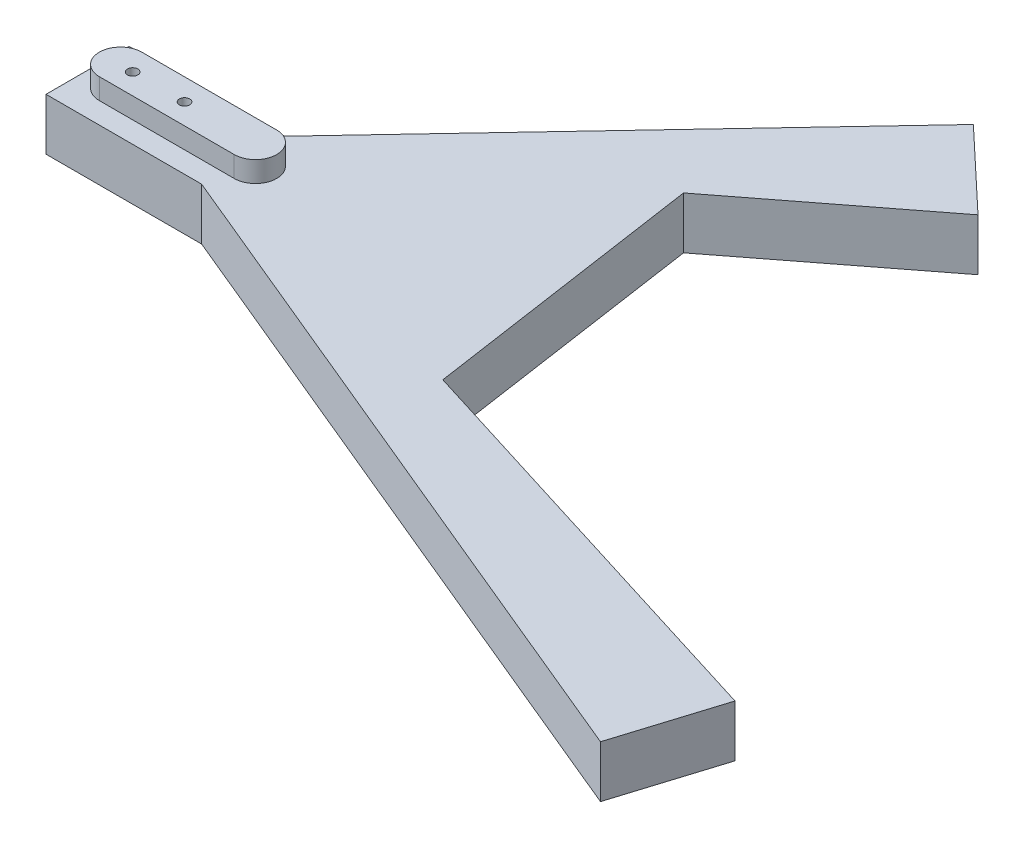
SolidWorks part; units mm, degrees
ref_plane "Front Plane" through (0, 0, 0) normal (0, 0, 1) x (1, 0, 0)
ref_plane "Top Plane" through (0, 0, 0) normal (0, 1, 0) x (1, 0, 0)
ref_plane "Right Plane" through (0, 0, 0) normal (1, 0, 0) x (0, 0, -1)
sketch "Sketch1" plane through (0, 0, 0) normal (0, 1, 0) x (1, 0, 0)
  line L0 (19.1887, 4.5283) -> (83.5984, 72.8611)
  line L1 (-10.8113, 4.5283) -> (19.1887, 4.5283)
  line L2 (-10.8113, 4.5283) -> (-10.8113, -11.4717)
  line L3 (-10.8113, -11.4717) -> (19.1887, -11.4717)
  line L4 (19.1887, 4.5283) -> (19.1887, -11.4717)
  line L5 (83.5984, 72.8611) -> (99.1264, 58.2245)
  line L6 (99.1264, 58.2245) -> (19.1887, -3.4717)
  line L7 (19.1887, -3.4717) -> (156.8481, -46.3414)
  line L8 (156.8481, -46.3414) -> (150.6929, -66.1064)
  line L9 (150.6929, -66.1064) -> (19.1887, -11.4717)
  line L10 (67.0937, 33.5015) -> (75.0843, -20.8786)
  dimension "D1" = 30
  dimension "D2" = 16
extrude "Boss-Extrude1" add sketch "Sketch1" along normal blind 10 contours L6 L5 L0 L4 | L9 L8 L7 L4 | L4 L1 L2 L3 | L10 L6 L7
sketch "Sketch2" plane through (0, 10, 0) normal (0, 1, 0) x (1, 0, 0)
  line L0 (-4.6164, -3.2944) -> (21.3836, -3.2944) construction
  line L1 (-4.6164, 0.7996) -> (21.3836, 0.7996)
  line L2 (-4.6164, -7.3884) -> (21.3836, -7.3884)
  arc A0 (-4.6164, 0.7996) -> (-4.6164, -7.3884) centre (-4.6164, -3.2944) ccw
  arc A1 (21.3836, -7.3884) -> (21.3836, 0.7996) centre (21.3836, -3.2944) ccw
  point P2 (8.3836, -3.2944)
  dimension "D1" = 26
extrude "Boss-Extrude2" add sketch "Sketch2" along normal blind 4
sketch "Sketch3" plane through (0, 14, 0) normal (0, 1, 0) x (1, 0, 0)
  line L0 (-4.6164, -7.3884) -> (21.3836, -7.3884) construction
  circle A0 centre (-2.1895, -3.3884) radius 1
  circle A1 centre (7.8105, -3.3942) radius 1
  dimension "D1" = 4
  dimension "D2" = 10
extrude "Cut-Extrude1" cut sketch "Sketch3" against normal blind 20
